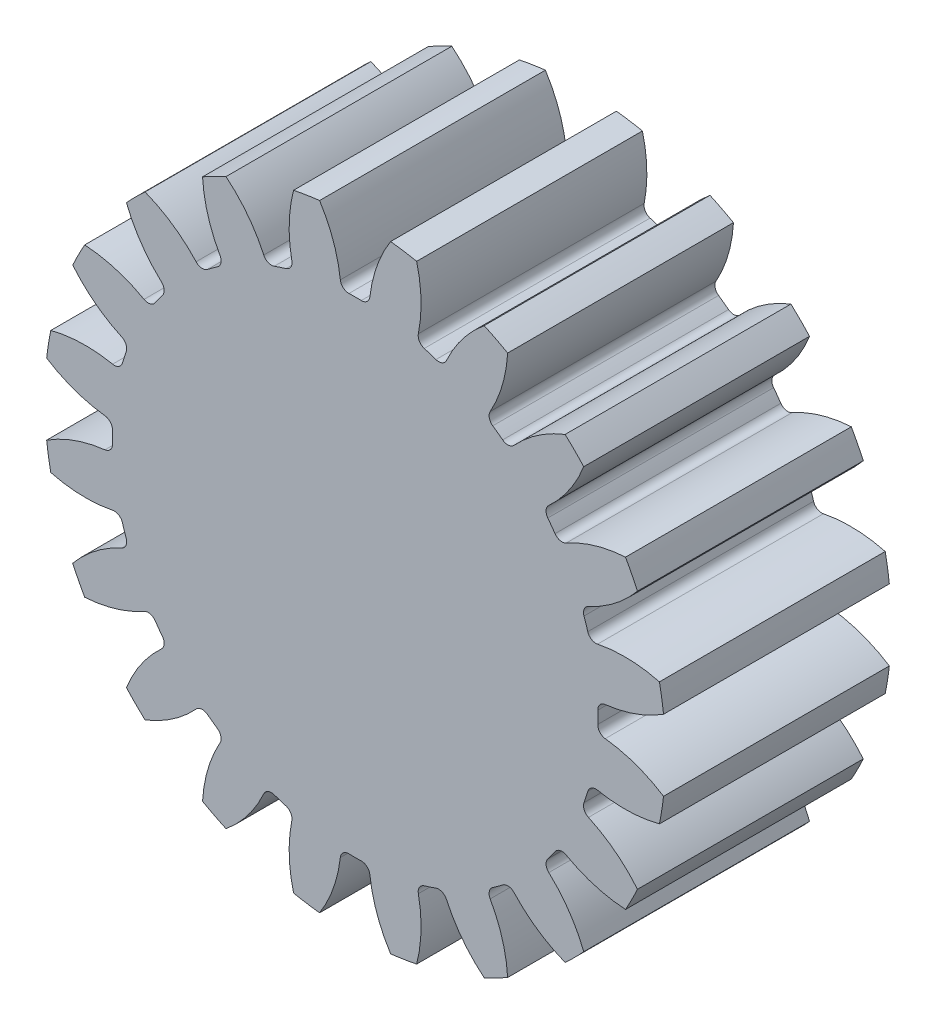
SolidWorks part; units mm, degrees
ref_plane "Спереди" through (0, 0, 0) normal (0, 0, 1) x (1, 0, 0)
ref_plane "Сверху" through (0, 0, 0) normal (0, 1, 0) x (1, 0, 0)
ref_plane "Справа" through (0, 0, 0) normal (1, 0, 0) x (0, 0, -1)
sketch "Эскиз3" plane through (0, 0, 0) normal (0, 0, 1) x (1, 0, 0)
  circle A0 centre (0, 0) radius 11
  circle A1 centre (0, 0) radius 10
  circle A2 centre (0, 0) radius 8.6
  dimension "D1" = 22
  dimension "D2" = 20
  dimension "D3" = 2.4
extrude "Бобышка-Вытянуть1" add sketch "Эскиз3" along normal blind 8 contours A0
sketch "Эскиз5" plane through (0, 0, 8) normal (0, 0, 1) x (1, 0, 0)
  line L0 (0, 0) -> (0, 11) construction
  line L1 (-0.499, 8.5855) -> (0, 0) construction
  line L2 (-0.7846, 9.9692) -> (0.7846, 9.9692) construction
  line L3 (0.7846, 9.9692) -> (2.3345, 9.7237) construction
  line L4 (-4.0926, 19.0578) -> (0.4525, 6.5704) construction
  line L5 (0, 0) -> (0.2455, 1.5499) construction
  circle A0 centre (0, 0) radius 11 construction
  arc A1 (-2.0035, 11.8316) -> (-0.499, 8.5855) centre (-5.3628, 8.3028) cw
  arc A2 (2.0035, 11.8316) -> (0.499, 8.5855) centre (5.3628, 8.3028) ccw
  circle A3 centre (0, 0) radius 8.6 construction
  circle A4 centre (0, 0) radius 8.6
  circle A6 centre (0, 0) radius 10 construction
  circle A7 centre (0, 0) radius 12
  circle A8 centre (0, 0) radius 12
  point P2 (0.7032, 14.0449)
  circle M8 centre (0, 0) radius 11
  dimension "D2" = 20
  dimension "D3" = 9
  dimension "D1" = 1
extrude "Вырез-Вытянуть1" cut sketch "Эскиз5" against normal through all both and the other way through all contours A2 A8 A1 M8 | A4 A2 A1 M8
fillet "Скругление1" radius 0.3 2 edges at (0.499, 8.5855, 4) (-0.499, 8.5855, 4)
pattern_circular "Круговой массив1" count 20 over 360 about axis through (0, 0, 0) along (0, 0, 1) of "Вырез-Вытянуть1", "Скругление1"
equation "\"модуль\"= 1"
equation "\"число зубьев\"= 20"
equation "\"D1@Эскиз3\"= ( \"число зубьев\" + 2 ) * \"модуль\""
equation "\"D2@Эскиз3\"=\"модуль\"*\"число зубьев\""
equation "\"D3@Эскиз3\"=\"модуль\"*if(\"модуль\">=1.25,2.25, 2.4)"
equation "\"ширина\" = 8"
equation "\"D1@Бобышка-Вытянуть1\"=\"ширина\""
equation "\"D3@Эскиз5\"=180/\"число зубьев\""
equation "\"радиус скругления основания зуба\" = 0.3"
equation "\"D1@Скругление1\"= \"радиус скругления основания зуба\" * \"модуль\""
equation "\"D1@Круговой массив1\" = \"число зубьев\""
